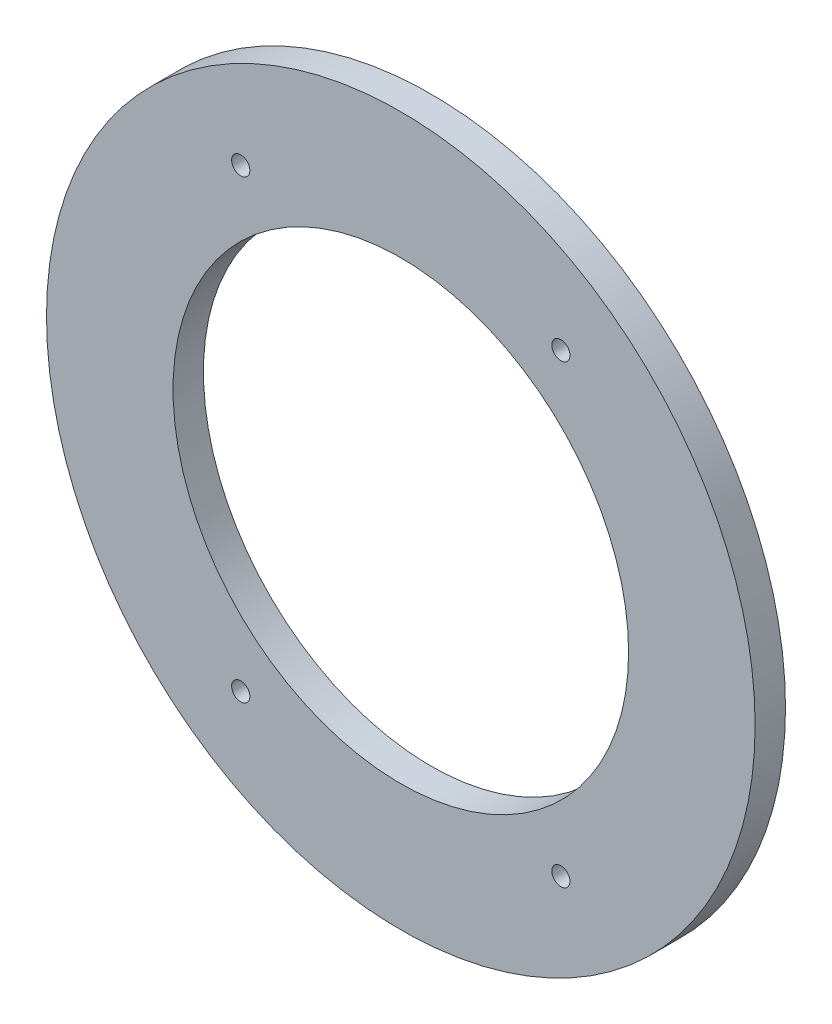
SolidWorks part; units mm, degrees
ref_plane "正面" through (0, 0, 0) normal (0, 0, 1) x (1, 0, 0)
ref_plane "平面" through (0, 0, 0) normal (0, 1, 0) x (1, 0, 0)
ref_plane "右側面" through (0, 0, 0) normal (1, 0, 0) x (0, 0, -1)
sketch "hub inported" plane through (0, 0, 0) normal (0, 0, 1) x (1, 0, 0)
  line L0 (50.56, 0) -> (55, 0)
  line L1 (49.2903, 11.2463) -> (53.62, 12.23)
  line L2 (39.53, 31.5199) -> (42.9999, 34.2899)
  line L3 (21.9345, 45.5492) -> (23.8599, 49.5499)
  line L4 (0, 50.56) -> (0, 55)
  line L5 (-21.9275, 45.5525) -> (-23.8599, 49.55)
  line L6 (-39.53, 31.5199) -> (-42.9999, 34.2899)
  line L7 (-49.2903, 11.2463) -> (-53.62, 12.23)
  line L8 (-49.2903, -11.2563) -> (-53.62, -12.24)
  line L9 (-39.53, -31.5199) -> (-42.9999, -34.2899)
  line L10 (-21.9345, -45.5492) -> (-23.86, -49.55)
  line L11 (0, -50.56) -> (0, -55)
  line L12 (21.9345, -45.5492) -> (23.8599, -49.5499)
  line L13 (39.53, -31.5299) -> (42.9999, -34.2999)
  line L14 (49.2903, -11.2463) -> (53.62, -12.23)
  line L15 (59.14, 0) -> (63.28, 0)
  line L16 (55, 0) -> (59.14, 0)
  line L17 (53.62, 12.23) -> (57.6571, 13.1472)
  line L18 (57.6571, 13.1472) -> (61.6942, 14.0644)
  line L19 (46.2354, 36.8728) -> (49.4709, 39.4557)
  line L20 (42.9999, 34.2899) -> (46.2354, 36.8728)
  line L21 (25.6553, 53.2804) -> (27.4507, 57.0109)
  line L22 (23.8599, 49.5499) -> (25.6553, 53.2804)
  line L23 (0, 55) -> (0, 59.14)
  line L24 (0, 59.14) -> (0, 63.28)
  line L25 (-25.6618, 53.2773) -> (-27.4637, 57.0046)
  line L26 (-23.8599, 49.55) -> (-25.6618, 53.2773)
  line L27 (-46.2354, 36.8728) -> (-49.4709, 39.4557)
  line L28 (-42.9999, 34.2899) -> (-46.2354, 36.8728)
  line L29 (-57.6571, 13.1472) -> (-61.6942, 14.0644)
  line L30 (-53.62, 12.23) -> (-57.6571, 13.1472)
  line L31 (-57.6571, -13.1572) -> (-61.6942, -14.0744)
  line L32 (-53.62, -12.24) -> (-57.6571, -13.1572)
  line L33 (-46.2354, -36.8728) -> (-49.4709, -39.4557)
  line L34 (-42.9999, -34.2899) -> (-46.2354, -36.8728)
  line L35 (-25.6553, -53.2804) -> (-27.4507, -57.0109)
  line L36 (-23.86, -49.55) -> (-25.6553, -53.2804)
  line L37 (0, -59.14) -> (0, -63.28)
  line L38 (0, -55) -> (0, -59.14)
  line L39 (25.6553, -53.2804) -> (27.4507, -57.0109)
  line L40 (23.8599, -49.5499) -> (25.6553, -53.2804)
  line L41 (46.2354, -36.8828) -> (49.4709, -39.4657)
  line L42 (42.9999, -34.2999) -> (46.2354, -36.8828)
  line L43 (57.6571, -13.1472) -> (61.6942, -14.0644)
  line L44 (53.62, -12.23) -> (57.6571, -13.1472)
  line L224 (-65.9318, 6.3318) -> (-66.3382, 6.3318)
  line L225 (-66.3382, 6.3318) -> (-66.3382, 5.4682)
  line L226 (-66.3382, 5.4682) -> (-65.9318, 5.4682)
  line L227 (-65.9318, 5.4682) -> (-65.9318, 6.3318)
  line L228 (-64.6618, 6.3318) -> (-65.0682, 6.3318)
  line L229 (-65.0682, 6.3318) -> (-65.0682, 5.4682)
  line L230 (-65.0682, 5.4682) -> (-64.6618, 5.4682)
  line L231 (-64.6618, 5.4682) -> (-64.6618, 6.3318)
  line L232 (-64.15, 6.45) -> (-65.15, 6.45)
  line L233 (-65.15, 6.45) -> (-65.15, 5.35)
  line L234 (-65.15, 5.35) -> (-64.15, 5.35)
  line L235 (-64.15, 5.35) -> (-64.15, 6.45)
  line L236 (-65.85, 6.45) -> (-66.85, 6.45)
  line L237 (-66.85, 6.45) -> (-66.85, 5.35)
  line L238 (-66.85, 5.35) -> (-65.85, 5.35)
  line L239 (-65.85, 5.35) -> (-65.85, 6.45)
  line L240 (-57.2682, -0.4318) -> (-56.8618, -0.4318)
  line L241 (-56.8618, -0.4318) -> (-56.8618, 0.4318)
  line L242 (-56.8618, 0.4318) -> (-57.2682, 0.4318)
  line L243 (-57.2682, 0.4318) -> (-57.2682, -0.4318)
  line L244 (-58.5382, -0.4318) -> (-58.1318, -0.4318)
  line L245 (-58.1318, -0.4318) -> (-58.1318, 0.4318)
  line L246 (-58.1318, 0.4318) -> (-58.5382, 0.4318)
  line L247 (-58.5382, 0.4318) -> (-58.5382, -0.4318)
  line L248 (-59.05, -0.55) -> (-58.05, -0.55)
  line L249 (-58.05, -0.55) -> (-58.05, 0.55)
  line L250 (-58.05, 0.55) -> (-59.05, 0.55)
  line L251 (-59.05, 0.55) -> (-59.05, -0.55)
  line L252 (-57.35, -0.55) -> (-56.35, -0.55)
  line L253 (-56.35, -0.55) -> (-56.35, 0.55)
  line L254 (-56.35, 0.55) -> (-57.35, 0.55)
  line L255 (-57.35, 0.55) -> (-57.35, -0.55)
  line L256 (-67.604, 2.504) -> (-67.604, 1.296)
  line L257 (-67.604, 1.296) -> (-66.396, 1.296)
  line L258 (-66.396, 1.296) -> (-66.396, 2.504)
  line L259 (-66.396, 2.504) -> (-67.604, 2.504)
  line L260 (-67.604, 2.504) -> (-67.604, 1.296)
  line L261 (-67.604, 1.296) -> (-66.396, 1.296)
  line L262 (-66.396, 1.296) -> (-66.396, 2.504)
  line L263 (-66.396, 2.504) -> (-67.604, 2.504)
  line L264 (-67.604, 0.504) -> (-67.604, -0.704)
  line L265 (-67.604, -0.704) -> (-66.396, -0.704)
  line L266 (-66.396, -0.704) -> (-66.396, 0.504)
  line L267 (-66.396, 0.504) -> (-67.604, 0.504)
  line L268 (-67.604, 0.504) -> (-67.604, -0.704)
  line L269 (-67.604, -0.704) -> (-66.396, -0.704)
  line L270 (-66.396, -0.704) -> (-66.396, 0.504)
  line L271 (-66.396, 0.504) -> (-67.604, 0.504)
  line L288 (-65.068, 5.544) -> (-65.932, 5.544)
  line L289 (-65.932, 6.256) -> (-65.068, 6.256)
  line L290 (-64.027, 6.883) -> (-66.973, 6.883)
  line L291 (-66.973, 6.883) -> (-66.973, 4.917)
  line L292 (-66.973, 4.917) -> (-64.027, 4.917)
  line L293 (-64.027, 4.917) -> (-64.027, 6.883)
  line L294 (-64.0174, 6.5992) -> (-67.0174, 6.5992)
  line L295 (-67.0174, 6.5992) -> (-67.0174, 5.1992)
  line L296 (-67.0174, 5.1992) -> (-64.0174, 5.1992)
  line L297 (-64.0174, 5.1992) -> (-64.0174, 6.5992)
  line L298 (-58.132, 0.356) -> (-57.268, 0.356)
  line L299 (-57.268, -0.356) -> (-58.132, -0.356)
  line L300 (-59.173, -0.983) -> (-56.227, -0.983)
  line L301 (-56.227, -0.983) -> (-56.227, 0.983)
  line L302 (-56.227, 0.983) -> (-59.173, 0.983)
  line L303 (-59.173, 0.983) -> (-59.173, -0.983)
  line L304 (-59.2, -0.7) -> (-56.2, -0.7)
  line L305 (-56.2, -0.7) -> (-56.2, 0.7)
  line L306 (-56.2, 0.7) -> (-59.2, 0.7)
  line L307 (-59.2, 0.7) -> (-59.2, -0.7)
  line L308 (31, 39) -> (23.8599, 49.5499)
  line L309 (42.9999, 34.2899) -> (31, 39)
  line L310 (53.62, 12.23) -> (42.9999, 34.2899)
  line L311 (55, 0) -> (53.62, 12.23)
  line L313 (53.62, -12.23) -> (55, 0)
  line L314 (42.9999, -34.2999) -> (53.62, -12.23)
  line L315 (42.9999, -34.2999) -> (30.1, -38)
  line L316 (-23.86, -49.55) -> (0, -55)
  line L317 (-30, -38) -> (-23.86, -49.55)
  line L318 (-42.9999, -34.2899) -> (-30, -38)
  line L319 (-53.62, -12.24) -> (-42.9999, -34.2899)
  line L320 (-53.62, 12.23) -> (-53.62, 0)
  line L321 (-53.62, 0) -> (-53.62, -12.24)
  line L322 (-42.9999, 34.2899) -> (-53.62, 12.23)
  line L323 (-30, 38) -> (-23.8599, 49.55)
  line L324 (-42.9999, 34.2899) -> (-30, 38)
  line L325 (23.8599, 49.5499) -> (0, 55)
  line L326 (-23.8599, 49.55) -> (0, 55)
  line L328 (30.1, -38) -> (23.8599, -49.5499)
  line L329 (-53.62, 0) -> (-58.55, 0)
  line L332 (-66.2545, 5.8992) -> (-67.0174, 5.2409)
  line L333 (-67.0174, 5.2409) -> (-67.0174, 1.8666)
  line L335 (23.8599, -49.5499) -> (0, -55)
  line L336 (-49.4709, -39.4557) -> (-27.4507, -57.0109)
  line L337 (-61.6942, -14.0744) -> (-49.4709, -39.4557)
  line L338 (-61.6942, 14.0644) -> (-61.6942, 5.8992)
  line L339 (-61.6942, 5.8992) -> (-61.6942, -14.0744)
  line L340 (-49.4709, 39.4557) -> (-61.6942, 14.0644)
  line L341 (-49.4709, 39.4557) -> (-27.4637, 57.0046)
  line L342 (-27.4637, 57.0046) -> (0, 63.28)
  line L343 (0, 63.28) -> (27.4507, 57.0109)
  line L344 (27.4507, 57.0109) -> (49.4709, 39.4557)
  line L345 (49.4709, -39.4657) -> (27.4507, -57.0109)
  line L346 (49.4709, -39.4657) -> (61.6942, -14.0644)
  line L347 (49.4709, 39.4557) -> (61.6942, 14.0644)
  line L348 (-27.4507, -57.0109) -> (0, -63.28)
  line L349 (27.4507, -57.0109) -> (0, -63.28)
  line L350 (61.6942, 14.0644) -> (63.28, 0)
  line L351 (61.6942, -14.0644) -> (63.28, 0)
  line L352 (-61.6942, 5.8992) -> (-64.0174, 5.8992)
  circle A0 centre (-31.623, -45) radius 1.8
  circle A1 centre (31.623, -45) radius 1.8
  circle A2 centre (31.625, 45) radius 1.8
  circle A3 centre (-31.623, 45) radius 1.8
  circle A4 centre (0, -50.56) radius 1.6
  circle A5 centre (0, -59.14) radius 0.7
  circle A6 centre (39.53, 31.5199) radius 1.6
  circle A7 centre (46.2354, 36.8728) radius 0.7
  circle A8 centre (-49.2903, 11.2463) radius 1.6
  circle A9 centre (-57.6571, 13.1472) radius 0.7
  circle A10 centre (-21.9345, -45.5492) radius 1.6
  circle A11 centre (-25.6553, -53.2804) radius 0.7
  circle A12 centre (49.2903, 11.2463) radius 1.6
  circle A13 centre (57.6571, 13.1472) radius 0.7
  circle A14 centre (-39.53, 31.5199) radius 1.6
  circle A15 centre (-46.2354, 36.8728) radius 0.7
  circle A16 centre (-39.53, -31.5199) radius 1.6
  circle A17 centre (-46.2354, -36.8728) radius 0.7
  circle A18 centre (49.2903, -11.2463) radius 1.6
  circle A19 centre (57.6571, -13.1472) radius 0.7
  circle A20 centre (-21.9275, 45.5525) radius 1.6
  circle A21 centre (-25.6618, 53.2773) radius 0.7
  circle A22 centre (-49.2903, -11.2563) radius 1.6
  circle A23 centre (-57.6571, -13.1572) radius 0.7
  circle A24 centre (39.53, -31.5299) radius 1.6
  circle A25 centre (46.2354, -36.8828) radius 0.7
  circle A26 centre (0, 50.56) radius 1.6
  circle A27 centre (0, 59.14) radius 0.7
  circle A28 centre (21.9345, 45.5492) radius 1.6
  circle A29 centre (25.6553, 53.2804) radius 0.7
  circle A30 centre (21.9345, -45.5492) radius 1.6
  circle A31 centre (25.6553, -53.2804) radius 0.7
  circle A32 centre (50.56, 0) radius 1.6
  circle A33 centre (59.14, 0) radius 0.7
  circle A34 centre (0, 0) radius 45
  circle A35 centre (0, 0) radius 70
  arc A56 (-57.268, 0.3179) -> (-57.268, 0.3941) centre (-57.268, 0.356) ccw
  arc A57 (-58.132, 0.3941) -> (-58.132, 0.3179) centre (-58.132, 0.356) ccw
  arc A58 (-58.132, -0.3179) -> (-58.132, -0.3941) centre (-58.132, -0.356) ccw
  arc A59 (-57.268, -0.3941) -> (-57.268, -0.3179) centre (-57.268, -0.356) ccw
  arc A60 (-56.227, -0.9957) -> (-56.227, -0.9703) centre (-56.227, -0.983) ccw
  arc A61 (-59.173, -0.9703) -> (-59.173, -0.9957) centre (-59.173, -0.983) ccw
  arc A62 (-56.2143, 0.983) -> (-56.2397, 0.983) centre (-56.227, 0.983) ccw
  arc A63 (-56.2397, -0.983) -> (-56.2143, -0.983) centre (-56.227, -0.983) ccw
  arc A64 (-59.173, 0.9957) -> (-59.173, 0.9703) centre (-59.173, 0.983) ccw
  arc A65 (-56.227, 0.9703) -> (-56.227, 0.9957) centre (-56.227, 0.983) ccw
  arc A66 (-59.1857, -0.983) -> (-59.1603, -0.983) centre (-59.173, -0.983) ccw
  arc A67 (-59.1603, 0.983) -> (-59.1857, 0.983) centre (-59.173, 0.983) ccw
  arc A68 (-56.2, -0.7318) -> (-56.2, -0.6683) centre (-56.2, -0.7001) ccw
  arc A69 (-59.2, -0.6683) -> (-59.2, -0.7318) centre (-59.2, -0.7001) ccw
  arc A70 (-56.1683, 0.7) -> (-56.2318, 0.7) centre (-56.2001, 0.7) ccw
  arc A71 (-56.2318, -0.7) -> (-56.1683, -0.7) centre (-56.2001, -0.7) ccw
  arc A72 (-59.2, 0.7318) -> (-59.2, 0.6683) centre (-59.2, 0.7001) ccw
  arc A73 (-56.2, 0.6683) -> (-56.2, 0.7318) centre (-56.2, 0.7001) ccw
  arc A74 (-59.2318, -0.7) -> (-59.1683, -0.7) centre (-59.2001, -0.7) ccw
  arc A75 (-59.1683, 0.7) -> (-59.2318, 0.7) centre (-59.2001, 0.7) ccw
  point P568 (42.9999, 34.2899)
  point P570 (-23.86, -49.55)
  point P581 (-65.5042, 5.8992)
  point P582 (-57.7, 0)
  point P583 (-67.0174, 0.983)
  dimension "D1" = 4.14
  dimension "D2" = 4.14
sketch "acrylic board sketch" plane through (0, 0, 0) normal (0, 0, 1) x (1, 0, 0)
  circle A0 centre (0, 0) radius 70 construction
  circle A1 centre (0, 0) radius 45 construction
  circle A2 centre (0, 0) radius 70
  circle A3 centre (0, 0) radius 45
  circle A4 centre (-31.623, 45) radius 1.8 construction
  circle A5 centre (31.625, 45) radius 1.8 construction
  circle A6 centre (31.623, -45) radius 1.8 construction
  circle A7 centre (-31.623, -45) radius 1.8 construction
  circle A8 centre (-31.623, 45) radius 1.8
  circle A9 centre (31.625, 45) radius 1.8
  circle A10 centre (31.623, -45) radius 1.8
  circle A11 centre (-31.623, -45) radius 1.8
extrude "acrylic board" add sketch "acrylic board sketch" along normal blind 6
sketch "wiring ditch 1 sketch" plane through (0, 0, 0) normal (0, 0, -1) x (-1, 0, 0)
  line L0 (-27.4507, 57.0109) -> (-49.4709, 39.4557) construction
  line L1 (-49.4709, 39.4557) -> (-61.6942, 14.0644) construction
  line L2 (-53.62, 12.23) -> (-42.9999, 34.2899) construction
  line L3 (-61.6942, 14.0644) -> (-63.28, 0) construction
  line L4 (-55, 0) -> (-53.62, 12.23) construction
  line L5 (-53.62, -12.23) -> (-55, 0) construction
  line L6 (-61.6942, -14.0644) -> (-63.28, 0) construction
  line L7 (-49.4709, -39.4657) -> (-61.6942, -14.0644) construction
  line L8 (-42.9999, -34.2999) -> (-53.62, -12.23) construction
  line L9 (-42.9999, -34.2999) -> (-30.1, -38) construction
  line L10 (-49.4709, -39.4657) -> (-27.4507, -57.0109) construction
  line L11 (-30.1, -38) -> (-23.8599, -49.5499) construction
  line L12 (-23.8599, -49.5499) -> (0, -55) construction
  line L13 (-27.4507, -57.0109) -> (0, -63.28) construction
  line L14 (23.86, -49.55) -> (0, -55) construction
  line L15 (27.4507, -57.0109) -> (0, -63.28) construction
  line L16 (49.4709, -39.4557) -> (27.4507, -57.0109) construction
  line L17 (42.9999, -34.2899) -> (30, -38) construction
  line L18 (30, -38) -> (23.86, -49.55) construction
  line L19 (53.62, -12.24) -> (42.9999, -34.2899) construction
  line L20 (61.6942, -14.0744) -> (49.4709, -39.4557) construction
  line L21 (61.6942, 5.8992) -> (61.6942, -14.0744) construction
  line L22 (53.62, 0) -> (53.62, -12.24) construction
  line L23 (53.62, 12.23) -> (53.62, 0) construction
  line L24 (61.6942, 14.0644) -> (61.6942, 5.8992) construction
  line L25 (49.4709, 39.4557) -> (61.6942, 14.0644) construction
  line L26 (42.9999, 34.2899) -> (53.62, 12.23) construction
  line L27 (49.4709, 39.4557) -> (27.4637, 57.0046) construction
  line L28 (42.9999, 34.2899) -> (30, 38) construction
  line L29 (30, 38) -> (23.8599, 49.55) construction
  line L30 (27.4637, 57.0046) -> (0, 63.28) construction
  line L31 (23.8599, 49.55) -> (0, 55) construction
  line L32 (0, 63.28) -> (-27.4507, 57.0109) construction
  line L33 (-23.8599, 49.5499) -> (0, 55) construction
  line L34 (-31, 39) -> (-23.8599, 49.5499) construction
  line L35 (-42.9999, 34.2899) -> (-31, 39) construction
  line L36 (-27.4507, 57.0109) -> (-49.4709, 39.4557)
  line L37 (-49.4709, 39.4557) -> (-61.6942, 14.0644)
  line L38 (-53.62, 12.23) -> (-42.9999, 34.2899)
  line L39 (-61.6942, 14.0644) -> (-63.28, 0)
  line L40 (-55, 0) -> (-53.62, 12.23)
  line L41 (-53.62, -12.23) -> (-55, 0)
  line L42 (-61.6942, -14.0644) -> (-63.28, 0)
  line L43 (-49.4709, -39.4657) -> (-61.6942, -14.0644)
  line L44 (-42.9999, -34.2999) -> (-53.62, -12.23)
  line L45 (-42.9999, -34.2999) -> (-30.1, -38)
  line L46 (-49.4709, -39.4657) -> (-27.4507, -57.0109)
  line L47 (-30.1, -38) -> (-23.8599, -49.5499)
  line L48 (-23.8599, -49.5499) -> (0, -55)
  line L49 (-27.4507, -57.0109) -> (0, -63.28)
  line L50 (23.86, -49.55) -> (0, -55)
  line L51 (27.4507, -57.0109) -> (0, -63.28)
  line L52 (49.4709, -39.4557) -> (27.4507, -57.0109)
  line L53 (42.9999, -34.2899) -> (30, -38)
  line L54 (30, -38) -> (23.86, -49.55)
  line L55 (53.62, -12.24) -> (42.9999, -34.2899)
  line L56 (61.6942, -14.0744) -> (49.4709, -39.4557)
  line L57 (61.6942, 5.8992) -> (61.6942, -14.0744)
  line L58 (53.62, 0) -> (53.62, -12.24)
  line L59 (53.62, 12.23) -> (53.62, 0)
  line L60 (61.6942, 14.0644) -> (61.6942, 5.8992)
  line L61 (49.4709, 39.4557) -> (61.6942, 14.0644)
  line L62 (42.9999, 34.2899) -> (53.62, 12.23)
  line L63 (49.4709, 39.4557) -> (27.4637, 57.0046)
  line L64 (42.9999, 34.2899) -> (30, 38)
  line L65 (30, 38) -> (23.8599, 49.55)
  line L66 (27.4637, 57.0046) -> (0, 63.28)
  line L67 (23.8599, 49.55) -> (0, 55)
  line L68 (0, 63.28) -> (-27.4507, 57.0109)
  line L69 (-23.8599, 49.5499) -> (0, 55)
  line L70 (-31, 39) -> (-23.8599, 49.5499)
  line L71 (-42.9999, 34.2899) -> (-31, 39)
  line L72 (-28.0737, 58.3046) -> (-50.5936, 40.351)
  line L73 (-50.5936, 40.351) -> (-63.0588, 14.4575)
  line L74 (-63.0588, 14.4575) -> (-64.6889, 0)
  line L75 (-63.0588, -14.4574) -> (-64.6889, 0)
  line L76 (-50.5936, -40.3612) -> (-63.0588, -14.4574)
  line L77 (-50.5936, -40.3612) -> (-28.0735, -58.3047)
  line L78 (-28.0735, -58.3047) -> (0, -64.716)
  line L79 (28.0737, -58.3046) -> (0, -64.716)
  line L80 (50.5935, -40.3511) -> (28.0737, -58.3046)
  line L81 (63.0942, -14.394) -> (50.5935, -40.3511)
  line L82 (63.0942, 5.8992) -> (63.0942, -14.394)
  line L83 (63.0942, 14.3839) -> (63.0942, 5.8992)
  line L84 (50.5937, 40.351) -> (63.0942, 14.3839)
  line L85 (50.5937, 40.351) -> (28.0868, 58.2983)
  line L86 (28.0868, 58.2983) -> (0.0001, 64.7161)
  line L87 (0.0001, 64.7161) -> (-28.0737, 58.3046)
  line L88 (-26.8276, 55.7171) -> (-48.3481, 38.5603)
  line L89 (-48.3481, 38.5603) -> (-60.3297, 13.6713)
  line L90 (-60.3297, 13.6713) -> (-61.8711, 0)
  line L91 (-60.3297, -13.6715) -> (-61.8711, 0)
  line L92 (-48.3481, -38.5702) -> (-60.3297, -13.6715)
  line L93 (-48.3481, -38.5702) -> (-26.8278, -55.717)
  line L94 (-26.8278, -55.717) -> (0, -61.844)
  line L95 (26.8276, -55.7171) -> (0, -61.844)
  line L96 (48.3482, -38.5602) -> (26.8276, -55.7171)
  line L97 (60.2942, -13.7549) -> (48.3482, -38.5602)
  line L98 (60.2942, 5.8992) -> (60.2942, -13.7549)
  line L99 (60.2942, 13.745) -> (60.2942, 5.8992)
  line L100 (48.3481, 38.5604) -> (60.2942, 13.745)
  line L101 (48.3481, 38.5604) -> (26.8405, 55.7109)
  line L102 (26.8405, 55.7109) -> (-0.0001, 61.8439)
  line L103 (-0.0001, 61.8439) -> (-26.8276, 55.7171)
  line L104 (-44.023, 35.3923) -> (-31.9159, 40.1445)
  line L105 (-31.9159, 40.1445) -> (-24.7099, 50.7919)
  line L106 (-24.7099, 50.7919) -> (0, 56.4361)
  line L107 (24.7957, 50.7723) -> (0, 56.4361)
  line L108 (30.9567, 39.1829) -> (24.7957, 50.7723)
  line L109 (43.9887, 35.4636) -> (30.9567, 39.1829)
  line L110 (43.9887, 35.4636) -> (55.02, 12.5494)
  line L111 (55.02, 12.5494) -> (55.02, 0)
  line L112 (55.02, 0) -> (55.02, -12.5596)
  line L113 (55.02, -12.5596) -> (43.9885, -35.4637)
  line L114 (43.9885, -35.4637) -> (30.9567, -39.1829)
  line L115 (30.9567, -39.1829) -> (24.7957, -50.7723)
  line L116 (24.7957, -50.7723) -> (0, -56.436)
  line L117 (-24.7901, -50.7735) -> (0, -56.436)
  line L118 (-31.0519, -39.1834) -> (-24.7901, -50.7735)
  line L119 (-43.9893, -35.4726) -> (-31.0519, -39.1834)
  line L120 (-43.9893, -35.4726) -> (-54.9845, -12.623)
  line L121 (-54.9845, -12.623) -> (-56.4089, 0)
  line L122 (-56.4089, 0) -> (-54.9845, 12.6231)
  line L123 (-54.9845, 12.6231) -> (-44.023, 35.3923)
  line L124 (-41.9769, 33.1875) -> (-30.0841, 37.8555)
  line L125 (-30.0841, 37.8555) -> (-23.01, 48.308)
  line L126 (-23.01, 48.308) -> (0, 53.5639)
  line L127 (22.9242, 48.3277) -> (0, 53.5639)
  line L128 (29.0433, 36.8171) -> (22.9242, 48.3277)
  line L129 (42.0112, 33.1162) -> (29.0433, 36.8171)
  line L130 (42.0112, 33.1162) -> (52.22, 11.9105)
  line L131 (52.22, 11.9105) -> (52.22, 0)
  line L132 (52.22, 0) -> (52.22, -11.9204)
  line L133 (52.22, -11.9204) -> (42.0113, -33.1162)
  line L134 (42.0113, -33.1162) -> (29.0433, -36.8171)
  line L135 (29.0433, -36.8171) -> (22.9242, -48.3277)
  line L136 (22.9242, -48.3277) -> (0, -53.5639)
  line L137 (-22.9297, -48.3264) -> (0, -53.5639)
  line L138 (-29.1481, -36.8166) -> (-22.9297, -48.3264)
  line L139 (-42.0106, -33.1273) -> (-29.1481, -36.8166)
  line L140 (-42.0106, -33.1273) -> (-52.2554, -11.837)
  line L141 (-52.2554, -11.837) -> (-53.5911, 0)
  line L142 (-53.5911, 0) -> (-52.2555, 11.8368)
  line L143 (-52.2555, 11.8368) -> (-41.9769, 33.1875)
  dimension "D1" = 1.4
  dimension "D2" = 1.4
  dimension "D3" = 1.4
  dimension "D4" = 1.4
extrude "wiring ditch 1" cut sketch "wiring ditch 1 sketch" against normal blind 0.5 contours L86 L87 L72 L73 L74 L75 L76 L77 L78 L79 L80 L81 L82 L83 L84 L85 L68 L66 L63 L61 L60 L57 L56 L52 L51 L49 L46 L43 L42 L39 L37 L36 | L66 L68 L36 L37 L39 L42 L43 L46 L49 L51 L52 L56 L57 L60 L61 L63 L103 L102 L101 L100 L99 L98 L97 L96 L95 L94 L93 L92 L91 L90 L89 L88 | L123 L122 L121 L120 L119 L118 L117 L116 L115 L114 L113 L112 L111 L110 L109 L108 L107 L106 L105 L104 L38 L71 L70 L69 L67 L65 L64 L62 L59 L58 L55 L53 L54 L50 L48 L47 L45 L44 L41 L40 | L71 L38 L40 L41 L44 L45 L47 L48 L50 L54 L53 L55 L58 L59 L62 L64 L65 L67 L69 L70 L142 L143 L124 L125 L126 L127 L128 L129 L130 L131 L132 L133 L134 L135 L136 L137 L138 L139 L140 L141
sketch "device ditch 1 sketch" plane through (0, 0, 0) normal (0, 0, -1) x (-1, 0, 0)
  circle A0 centre (57.6571, 13.1472) radius 0.7 construction
  circle A1 centre (46.2354, 36.8728) radius 0.7 construction
  circle A2 centre (25.6618, 53.2773) radius 0.7 construction
  circle A3 centre (0, 59.14) radius 0.7 construction
  circle A4 centre (-25.6553, 53.2804) radius 0.7 construction
  circle A5 centre (-46.2354, 36.8728) radius 0.7 construction
  circle A6 centre (-57.6571, 13.1472) radius 0.7 construction
  circle A7 centre (-59.14, 0) radius 0.7 construction
  circle A8 centre (-57.6571, -13.1472) radius 0.7 construction
  circle A9 centre (-46.2354, -36.8828) radius 0.7 construction
  circle A10 centre (-25.6553, -53.2804) radius 0.7 construction
  circle A11 centre (0, -59.14) radius 0.7 construction
  circle A12 centre (25.6553, -53.2804) radius 0.7 construction
  circle A13 centre (46.2354, -36.8728) radius 0.7 construction
  circle A14 centre (57.6571, -13.1572) radius 0.7 construction
  circle A15 centre (57.6571, 13.1472) radius 0.7
  circle A16 centre (46.2354, 36.8728) radius 0.7
  circle A17 centre (25.6618, 53.2773) radius 0.7
  circle A18 centre (0, 59.14) radius 0.7
  circle A19 centre (-25.6553, 53.2804) radius 0.7
  circle A20 centre (-46.2354, 36.8728) radius 0.7
  circle A21 centre (-57.6571, 13.1472) radius 0.7
  circle A22 centre (-59.14, 0) radius 0.7
  circle A23 centre (-57.6571, -13.1472) radius 0.7
  circle A24 centre (-46.2354, -36.8828) radius 0.7
  circle A25 centre (-25.6553, -53.2804) radius 0.7
  circle A26 centre (0, -59.14) radius 0.7
  circle A27 centre (25.6553, -53.2804) radius 0.7
  circle A28 centre (46.2354, -36.8728) radius 0.7
  circle A29 centre (57.6571, -13.1572) radius 0.7
  circle A30 centre (0, 50.56) radius 1.8
  circle A31 centre (21.9372, 45.553) radius 1.8
  circle A32 centre (39.5294, 31.5236) radius 1.8
  circle A33 centre (49.2924, 11.2507) radius 1.8
  circle A34 centre (49.2924, -11.2507) radius 1.8
  circle A35 centre (39.5294, -31.5236) radius 1.8
  circle A36 centre (21.9372, -45.553) radius 1.8
  circle A37 centre (0, -50.56) radius 1.8
  circle A38 centre (-21.9372, -45.553) radius 1.8
  circle A39 centre (-39.5294, -31.5236) radius 1.8
  circle A40 centre (-49.2924, -11.2507) radius 1.8
  circle A41 centre (-49.2924, 11.2507) radius 1.8
  circle A42 centre (-39.5294, 31.5236) radius 1.8
  circle A43 centre (-21.9372, 45.553) radius 1.8
  circle A44 centre (-50.56, 0) radius 1.8
  circle A45 centre (0, 63.28) radius 1.4
  circle A46 centre (0, 55) radius 1.4
  circle A47 centre (23.8636, 49.5533) radius 1.4
  circle A48 centre (27.4562, 57.0133) radius 1.4
  circle A49 centre (43.0007, 34.2919) radius 1.4
  circle A50 centre (49.4743, 39.4544) radius 1.4
  circle A51 centre (53.621, 12.2387) radius 1.4
  circle A52 centre (61.6934, 14.0811) radius 1.4
  circle A53 centre (53.621, -12.2387) radius 1.4
  circle A54 centre (61.6934, -14.0811) radius 1.4
  circle A55 centre (43.0007, -34.2919) radius 1.4
  circle A56 centre (49.4743, -39.4544) radius 1.4
  circle A57 centre (23.8636, -49.5533) radius 1.4
  circle A58 centre (27.4562, -57.0133) radius 1.4
  circle A59 centre (0, -55) radius 1.4
  circle A60 centre (0, -63.28) radius 1.4
  circle A61 centre (-23.8636, -49.5533) radius 1.4
  circle A62 centre (-27.4562, -57.0133) radius 1.4
  circle A63 centre (-43.0007, -34.2919) radius 1.4
  circle A64 centre (-49.4743, -39.4544) radius 1.4
  circle A65 centre (-53.621, -12.2387) radius 1.4
  circle A66 centre (-61.6934, -14.0811) radius 1.4
  circle A67 centre (-53.621, 12.2387) radius 1.4
  circle A68 centre (-61.6934, 14.0811) radius 1.4
  circle A69 centre (-43.0007, 34.2919) radius 1.4
  circle A70 centre (-49.4743, 39.4544) radius 1.4
  circle A71 centre (-23.8636, 49.5533) radius 1.4
  circle A72 centre (-27.4562, 57.0133) radius 1.4
  circle A73 centre (-63.28, 0) radius 1.4
  circle A74 centre (-55, 0) radius 1.4
  point P77 (0, 0)
  point P141 (0, 0)
  dimension "D1" = 3.6
  dimension "D3" = 3.6
  dimension "D4" = 2.8
  dimension "D5" = 2.8
  dimension "D7" = 2.8
  dimension "D8" = 2.8
  dimension "D2" = 14
  dimension "D6" = 14
extrude "device ditch 1" cut sketch "device ditch 1 sketch" against normal blind 3.5
sketch "device ditch 2 sketch" plane through (0, 0, 0) normal (0, 0, -1) x (-1, 0, 0)
  line L0 (66.396, 1.296) -> (66.396, 2.504) construction
  line L1 (55.7, 1.483) -> (59.7, 1.483)
  line L2 (55.7, 1.483) -> (55.7, -1.483)
  line L3 (55.7, -1.483) -> (59.7, -1.483)
  line L4 (59.7, 1.483) -> (59.7, -1.483)
  line L5 (65.896, 3.004) -> (68.104, 3.004)
  line L6 (65.896, 3.004) -> (65.896, -3.004)
  line L7 (65.896, -1.204) -> (68.104, -1.204)
  line L8 (68.104, 3.004) -> (68.104, -3.004)
  line L9 (63.5174, 7.383) -> (67.5174, 7.383)
  line L10 (63.5174, 7.383) -> (63.5174, 4.417)
  line L11 (63.5174, 4.417) -> (67.5174, 4.417)
  line L12 (67.5174, 7.383) -> (67.5174, 4.417)
  line L13 (67.604, 2.504) -> (67.604, 1.296) construction
  line L14 (67.604, -0.704) -> (66.396, -0.704) construction
  line L15 (66.396, 2.504) -> (67.604, 2.504) construction
  line L16 (64.027, 6.883) -> (66.973, 6.883) construction
  line L17 (66.973, 4.917) -> (64.027, 4.917) construction
  line L18 (67.0174, 6.5992) -> (67.0174, 5.1992) construction
  line L19 (64.0174, 5.1992) -> (64.0174, 6.5992) construction
  line L20 (56.227, 0.983) -> (59.173, 0.983) construction
  line L21 (59.173, -0.983) -> (56.227, -0.983) construction
  line L22 (59.2, 0.7) -> (59.2, -0.7) construction
  line L23 (56.2, -0.7) -> (56.2, 0.7) construction
  line L24 (0, 0) -> (82.4969, 0)
  line L25 (63.5174, -7.383) -> (63.5174, -4.417)
  line L26 (63.5174, -4.417) -> (67.5174, -4.417)
  line L27 (67.5174, -7.383) -> (67.5174, -4.417)
  line L28 (63.5174, -7.383) -> (67.5174, -7.383)
  line L29 (65.896, 0) -> (65.896, -1.204)
  line L30 (68.104, 0) -> (68.104, -1.204)
  line L31 (65.896, -3.004) -> (68.104, -3.004)
  line L32 (65.896, 1.204) -> (68.104, 1.204)
  dimension "D1" = 0.5
  dimension "D2" = 0.5
  dimension "D3" = 0.5
  dimension "D4" = 0.5
  dimension "D5" = 0.5
  dimension "D6" = 0.5
  dimension "D7" = 0.5
  dimension "D8" = 0.5
  dimension "D9" = 0.5
  dimension "D10" = 0.5
  dimension "D11" = 0.5
  dimension "D12" = 0.5
extrude "device ditch 2" cut sketch "device ditch 2 sketch" against normal blind 1.5 contours L2 L24 L4 L1 | L24 L2 L3 L4 | L32 L6 L24 L8 | L24 L6 L7 L8 | L6 L31 L8 L7 | L25 L28 L27 L26
sketch "wiring ditch 2 sketch" plane through (0, 0, 0) normal (0, 0, -1) x (-1, 0, 0)
  line L0 (65.896, -3.004) -> (65.896, -4.417)
  line L1 (67.5174, -4.417) -> (67.5174, -3.004)
  line L3 (55.7, 1.483) -> (55.7, -1.483) construction
  line L4 (55.02, 12.1844) -> (55.02, -12.1844) construction
  line L5 (63.5174, -7.383) -> (63.5174, -4.417) construction
  line L6 (63.0942, 14.3839) -> (63.0942, -14.394) construction
  line L7 (65.896, -3.004) -> (68.104, -3.004) construction
  line L12 (55.7, 1.483) -> (55.7, -1.483)
  line L13 (55.02, 1.483) -> (55.02, -1.483)
  line L14 (63.5174, -7.383) -> (63.5174, -4.417)
  line L15 (63.0942, -4.417) -> (63.0942, -7.383)
  line L16 (65.896, -3.004) -> (67.5174, -3.004)
  line L18 (55.7, 1.483) -> (55.02, 1.483)
  line L21 (55.7, -1.483) -> (55.02, -1.483)
  line L22 (63.5174, -4.417) -> (63.0942, -4.417)
  line L23 (63.5174, -7.383) -> (63.0942, -7.383)
  line L27 (65.896, -4.417) -> (67.5174, -4.417)
  circle A1 centre (0, 0) radius 70
  circle A2 centre (0, 0) radius 70
  dimension "D1" = 0
extrude "wiring ditch 2" cut sketch "wiring ditch 2 sketch" against normal blind 0.5 contours L0 L27 L1 L16 | L23 L14 L22 L15 | L21 L12 L18 L13
